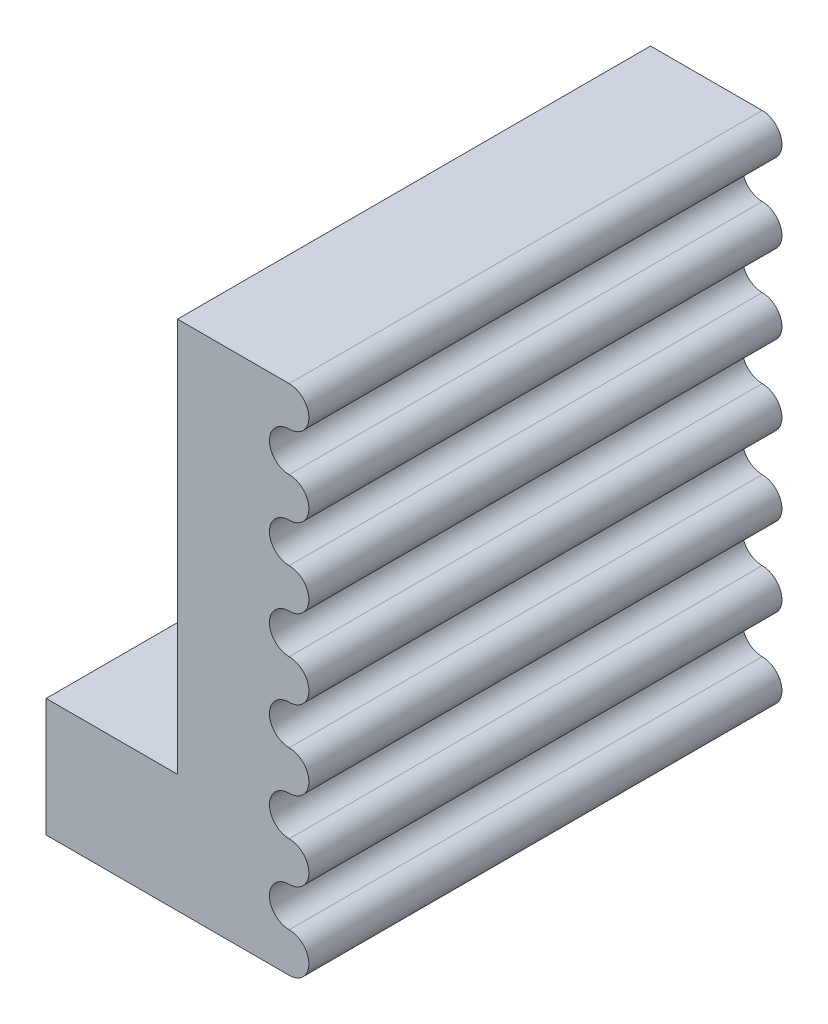
SolidWorks part; units mm, degrees
material "ABS"
ref_plane "前视基准面" through (0, 0, 0) normal (0, 0, 1) x (1, 0, 0)
ref_plane "上视基准面" through (0, 0, 0) normal (0, 1, 0) x (1, 0, 0)
ref_plane "右视基准面" through (0, 0, 0) normal (1, 0, 0) x (0, 0, -1)
other "Configuration Table"
sketch "草图1" plane through (0, 0, 0) normal (0, 0, 1) x (1, 0, 0)
  line L2 (5, 4.5) -> (5, 19.5)
  line L3 (5, 19.5) -> (9.25, 19.5)
  line L5 (0, 0) -> (0, 4.5)
  line L6 (0, 4.5) -> (5, 4.5)
  line L7 (9.25, 0) -> (0, 0)
  arc A0 (9.25, 18) -> (9.25, 19.5) centre (9.25, 18.75) ccw
  arc A1 (9.25, 18) -> (9.25, 16.5) centre (9.25, 17.25) ccw
  arc A2 (9.25, 15) -> (9.25, 16.5) centre (9.25, 15.75) ccw
  arc A3 (9.25, 15) -> (9.25, 13.5) centre (9.25, 14.25) ccw
  arc A4 (9.25, 12) -> (9.25, 13.5) centre (9.25, 12.75) ccw
  arc A5 (9.25, 12) -> (9.25, 10.5) centre (9.25, 11.25) ccw
  arc A6 (9.25, 9) -> (9.25, 10.5) centre (9.25, 9.75) ccw
  arc A7 (9.25, 9) -> (9.25, 7.5) centre (9.25, 8.25) ccw
  arc A8 (9.25, 6) -> (9.25, 7.5) centre (9.25, 6.75) ccw
  arc A9 (9.25, 6) -> (9.25, 4.5) centre (9.25, 5.25) ccw
  arc A10 (9.25, 3) -> (9.25, 4.5) centre (9.25, 3.75) ccw
  arc A11 (9.25, 3) -> (9.25, 1.5) centre (9.25, 2.25) ccw
  arc A12 (9.25, 0) -> (9.25, 1.5) centre (9.25, 0.75) ccw
  point P0 (0, 0)
  dimension "D3" = 9.25
  dimension "D1" = 0.75
  dimension "D2" = 5
extrude "凸台-拉伸1" add sketch "草图1" along normal blind 18
